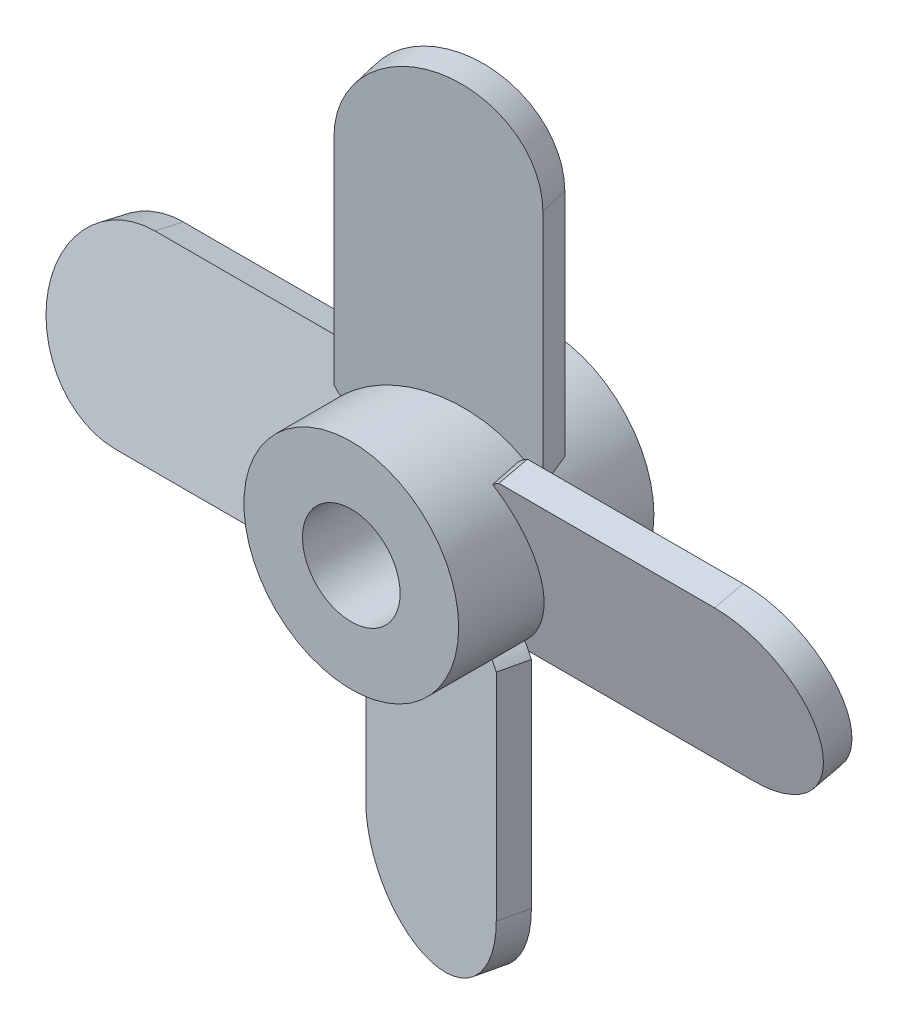
SolidWorks part; units mm, degrees
ref_plane "Front Plane" through (0, 0, 0) normal (0, 0, 1) x (1, 0, 0)
ref_plane "Top Plane" through (0, 0, 0) normal (0, 1, 0) x (1, 0, 0)
ref_plane "Right Plane" through (0, 0, 0) normal (1, 0, 0) x (0, 0, -1)
sketch "Sketch2" plane through (0, 0, 0) normal (0, 0, 1) x (1, 0, 0)
  circle A0 centre (0, 0) radius 5.5
  circle A1 centre (0, 0) radius 2.5
  dimension "D1" = 11
  dimension "D2" = 5
extrude "Boss-Extrude1" add sketch "Sketch2" along normal blind 10
sketch "Sketch3" plane through (0, 0, 0) normal (1, 0, 0) x (0, 0, -1)
  line L0 (-10, 0) -> (0, 0) construction
  line L1 (-10, 5.5) -> (-10, -5.5) construction
  line L2 (-5, 5.5) -> (-5, -5.5) construction
  line L3 (0, 5.5) -> (-10, 5.5) construction
  line L4 (-10, -5.5) -> (0, -5.5) construction
  line L5 (-3.7302, -5.5) -> (-6.4301, 6.1943) construction
  point P13 (-5, 0)
  dimension "D1" = 13
ref_plane "Plane1" through (0, -1.0959, 4.747) normal (0, 0.225, -0.9744) x (0, 0.9744, 0.225)
sketch "Sketch4" plane through (0, -1.0959, 4.747) normal (0, 0.225, -0.9744) x (0, 0.9744, 0.225)
  line L0 (5.562, 4.2894) -> (5.562, 15.3387)
  line L1 (-3.3562, 3.0722) -> (-3.3562, 15.3387)
  arc A0 (-3.3562, 3.0722) -> (0.5204, 3.2312) centre (-1.3384, 1.2134) cw
  arc A1 (0.5204, 3.2312) -> (5.562, 4.2894) centre (2.5121, 6.2811) ccw
  arc A2 (5.562, 15.3387) -> (-3.3562, 15.3387) centre (1.1029, 15.3387) ccw
extrude "Boss-Extrude2" add sketch "Sketch4" along normal mid plane 1.5
pattern_circular "CirPattern1" count 4 over 360 about axis through (0, 0, 0) along (0, 0, 1) of "Boss-Extrude2"
